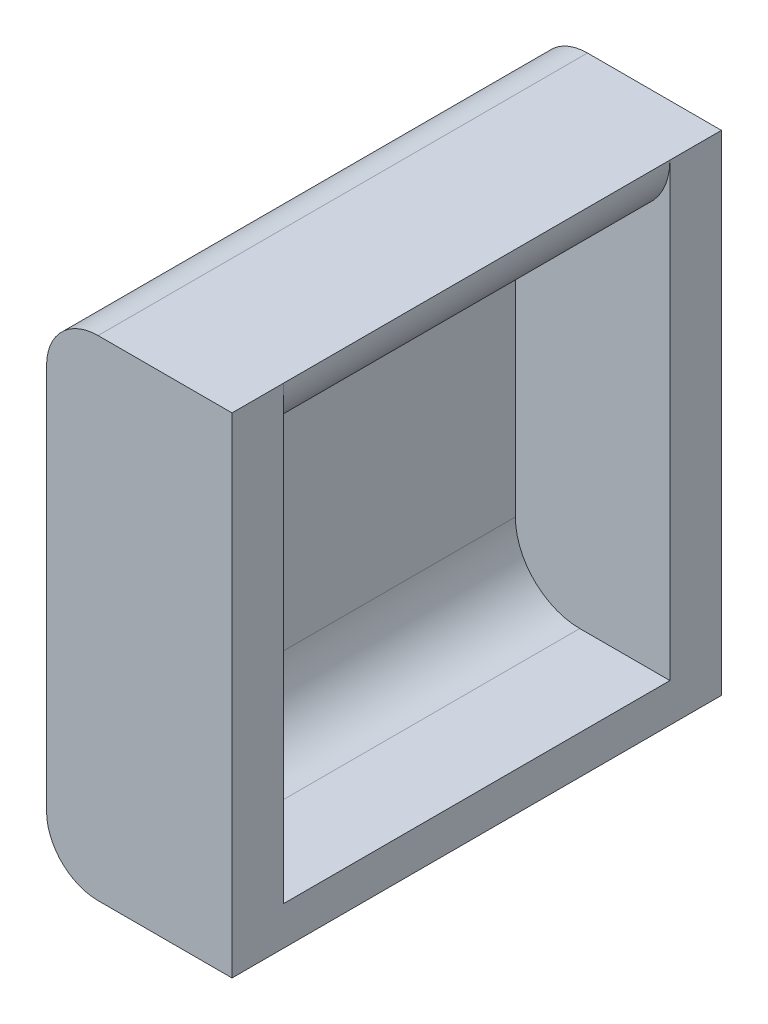
SolidWorks part; units mm, degrees
ref_plane "Front Plane" through (0, 0, 0) normal (0, 0, 1) x (1, 0, 0)
ref_plane "Top Plane" through (0, 0, 0) normal (0, 1, 0) x (1, 0, 0)
ref_plane "Right Plane" through (0, 0, 0) normal (1, 0, 0) x (0, 0, -1)
sketch "Sketch1" plane through (0, 0, 0) normal (0, 0, 1) x (1, 0, 0)
  line L0 (-19.812, -24.5745) -> (-19.812, -48.7045)
  line L1 (-19.812, -48.7045) -> (-28.956, -48.7045)
  line L2 (-28.956, -48.7045) -> (-28.956, -24.5745)
  line L3 (-28.956, -24.5745) -> (-19.812, -24.5745)
  line L8 (-35.56, 43.6245) -> (-35.56, 35.4965)
  line L9 (-32.385, 32.3215) -> (-22.987, 32.3215)
  line L10 (-19.812, 29.1465) -> (-19.812, -24.5745)
  line L11 (-22.987, -27.7495) -> (-24.257, -27.7495)
  line L12 (-27.432, -30.9245) -> (-27.432, -43.6245)
  line L13 (-24.257, -46.7995) -> (-3.175, -46.7995)
  line L14 (0, -43.6245) -> (0, 43.6245)
  line L15 (-3.175, 46.7995) -> (-32.385, 46.7995)
  line L16 (-35.56, 43.6245) -> (-35.56, 35.4965)
  line L17 (-32.385, 32.3215) -> (-22.987, 32.3215)
  line L18 (-19.812, 29.1465) -> (-19.812, -24.5745)
  line L19 (-22.987, -27.7495) -> (-24.257, -27.7495)
  line L20 (-27.432, -30.9245) -> (-27.432, -43.6245)
  line L21 (-24.257, -46.7995) -> (-3.175, -46.7995)
  line L22 (0, -43.6245) -> (0, 43.6245)
  line L23 (-3.175, 46.7995) -> (-32.385, 46.7995)
  arc A8 (-32.385, 46.7995) -> (-35.56, 43.6245) centre (-32.385, 43.6245) ccw
  arc A9 (-35.56, 35.4965) -> (-32.385, 32.3215) centre (-32.385, 35.4965) ccw
  arc A10 (-19.812, 29.1465) -> (-22.987, 32.3215) centre (-22.987, 29.1465) ccw
  arc A11 (-22.987, -27.7495) -> (-19.812, -24.5745) centre (-22.987, -24.5745) ccw
  arc A12 (-24.257, -27.7495) -> (-27.432, -30.9245) centre (-24.257, -30.9245) ccw
  arc A13 (-27.432, -43.6245) -> (-24.257, -46.7995) centre (-24.257, -43.6245) ccw
  arc A14 (-3.175, -46.7995) -> (0, -43.6245) centre (-3.175, -43.6245) ccw
  arc A15 (0, 43.6245) -> (-3.175, 46.7995) centre (-3.175, 43.6245) ccw
  arc A16 (-32.385, 46.7995) -> (-35.56, 43.6245) centre (-32.385, 43.6245) ccw
  arc A17 (-35.56, 35.4965) -> (-32.385, 32.3215) centre (-32.385, 35.4965) ccw
  arc A18 (-19.812, 29.1465) -> (-22.987, 32.3215) centre (-22.987, 29.1465) ccw
  arc A19 (-22.987, -27.7495) -> (-19.812, -24.5745) centre (-22.987, -24.5745) ccw
  arc A20 (-24.257, -27.7495) -> (-27.432, -30.9245) centre (-24.257, -30.9245) ccw
  arc A21 (-27.432, -43.6245) -> (-24.257, -46.7995) centre (-24.257, -43.6245) ccw
  arc A22 (-3.175, -46.7995) -> (0, -43.6245) centre (-3.175, -43.6245) ccw
  arc A23 (0, 43.6245) -> (-3.175, 46.7995) centre (-3.175, 43.6245) ccw
  dimension "D2" = 1.524
  dimension "D3" = 24.13
  dimension "D1" = 0
extrude "Boss-Extrude1" add sketch "Sketch1" against normal blind 19.05 contours A21 L20 A20 L19 A19 L3 L2 L1 L0 L21
sketch "Sketch2" plane through (0, 0, 0) normal (0, 0, 1) x (1, 0, 0)
  line L0 (-19.812, -24.5745) -> (-19.812, -48.7045)
  line L1 (-28.956, -48.7045) -> (-28.956, -24.5745)
  line L2 (-28.956, -24.5745) -> (-29.0357, -24.5594)
  line L7 (-27.432, -43.6245) -> (-27.432, -30.9245)
  line L8 (-24.257, -27.7495) -> (-22.987, -27.7495)
  line L9 (-19.812, -24.5745) -> (-28.956, -24.5745)
  line L10 (-28.956, -24.5745) -> (-28.956, -48.7045)
  line L11 (-28.956, -48.7045) -> (-19.812, -48.7045)
  line L12 (-19.812, -48.7045) -> (-19.812, -46.7995)
  line L13 (-19.812, -46.7995) -> (-24.257, -46.7995)
  line L14 (-27.432, -43.6245) -> (-27.432, -30.9245)
  line L15 (-24.257, -27.7495) -> (-22.987, -27.7495)
  line L16 (-19.812, -24.5745) -> (-28.956, -24.5745)
  line L17 (-28.956, -24.5745) -> (-28.956, -48.7045)
  line L18 (-28.956, -48.7045) -> (-19.812, -48.7045)
  line L19 (-19.812, -48.7045) -> (-19.812, -46.7995)
  line L20 (-19.812, -46.7995) -> (-24.257, -46.7995)
  arc A3 (-27.432, -43.6245) -> (-24.257, -46.7995) centre (-24.257, -43.6245) ccw
  arc A4 (-24.257, -27.7495) -> (-27.432, -30.9245) centre (-24.257, -30.9245) ccw
  arc A5 (-22.987, -27.7495) -> (-19.812, -24.5745) centre (-22.987, -24.5745) ccw
  arc A6 (-27.432, -43.6245) -> (-24.257, -46.7995) centre (-24.257, -43.6245) ccw
  arc A7 (-24.257, -27.7495) -> (-27.432, -30.9245) centre (-24.257, -30.9245) ccw
  arc A8 (-22.987, -27.7495) -> (-19.812, -24.5745) centre (-22.987, -24.5745) ccw
  arc M11 (-24.257, -46.7995) -> (-27.432, -43.6245) centre (-24.257, -43.6245) cw
  line M12 (-27.432, -43.6245) -> (-27.432, -30.9245)
  arc M13 (-27.432, -30.9245) -> (-24.257, -27.7495) centre (-24.257, -30.9245) cw
  line M14 (-24.257, -27.7495) -> (-22.987, -27.7495)
  arc M15 (-22.987, -27.7495) -> (-19.812, -24.5745) centre (-22.987, -24.5745) ccw
  line M16 (-19.812, -24.5745) -> (-28.956, -24.5745)
  line M17 (-28.956, -24.5745) -> (-28.956, -48.7045)
  line M18 (-28.956, -48.7045) -> (-19.812, -48.7045)
  line M19 (-19.812, -48.7045) -> (-19.812, -46.7995)
  line M20 (-19.812, -46.7995) -> (-24.257, -46.7995)
  dimension "D1" = 0
extrude "Boss-Extrude2" add sketch "Sketch2" along normal blind 2.54 contours M20 M11 M12 M13 M14 M15 M16 M17 M18 M19 | L0 M15 M14 M13 M12 M11 M20
sketch "Sketch3" plane through (0, 0, -19.05) normal (0, 0, -1) x (-1, 0, 0)
  line L0 (19.812, -24.5745) -> (19.812, -48.7045)
  line L1 (28.956, -48.7045) -> (28.956, -24.5745)
  line L7 (24.257, -46.7995) -> (19.812, -46.7995)
  line L8 (19.812, -46.7995) -> (19.812, -48.7045)
  line L9 (19.812, -48.7045) -> (28.956, -48.7045)
  line L10 (28.956, -48.7045) -> (28.956, -24.5745)
  line L11 (28.956, -24.5745) -> (19.812, -24.5745)
  line L12 (22.987, -27.7495) -> (24.257, -27.7495)
  line L13 (27.432, -30.9245) -> (27.432, -43.6245)
  line L14 (24.257, -46.7995) -> (19.812, -46.7995)
  line L15 (19.812, -46.7995) -> (19.812, -48.7045)
  line L16 (19.812, -48.7045) -> (28.956, -48.7045)
  line L17 (28.956, -48.7045) -> (28.956, -24.5745)
  line L18 (28.956, -24.5745) -> (19.812, -24.5745)
  line L19 (22.987, -27.7495) -> (24.257, -27.7495)
  line L20 (27.432, -30.9245) -> (27.432, -43.6245)
  arc A3 (24.257, -46.7995) -> (27.432, -43.6245) centre (24.257, -43.6245) ccw
  arc A4 (19.812, -24.5745) -> (22.987, -27.7495) centre (22.987, -24.5745) ccw
  arc A5 (27.432, -30.9245) -> (24.257, -27.7495) centre (24.257, -30.9245) ccw
  arc A6 (24.257, -46.7995) -> (27.432, -43.6245) centre (24.257, -43.6245) ccw
  arc A7 (19.812, -24.5745) -> (22.987, -27.7495) centre (22.987, -24.5745) ccw
  arc A8 (27.432, -30.9245) -> (24.257, -27.7495) centre (24.257, -30.9245) ccw
  arc M11 (27.432, -43.6245) -> (24.257, -46.7995) centre (24.257, -43.6245) cw
  line M12 (24.257, -46.7995) -> (19.812, -46.7995)
  line M13 (19.812, -46.7995) -> (19.812, -48.7045)
  line M14 (19.812, -48.7045) -> (28.956, -48.7045)
  line M15 (28.956, -48.7045) -> (28.956, -24.5745)
  line M16 (28.956, -24.5745) -> (19.812, -24.5745)
  arc M17 (19.812, -24.5745) -> (22.987, -27.7495) centre (22.987, -24.5745) ccw
  line M18 (22.987, -27.7495) -> (24.257, -27.7495)
  arc M19 (24.257, -27.7495) -> (27.432, -30.9245) centre (24.257, -30.9245) cw
  line M20 (27.432, -30.9245) -> (27.432, -43.6245)
  dimension "D1" = 0
extrude "Boss-Extrude3" add sketch "Sketch3" along normal blind 2.54 contours L0 M17 M12 M11 M20 M19 M18 | M20 M11 M12 M13 M14 M15 M16 M17 M18 M19
fillet "Fillet1" radius 2.54 2 edges at (-28.956, -48.7045, -9.525) (-28.956, -24.5745, -9.525)
